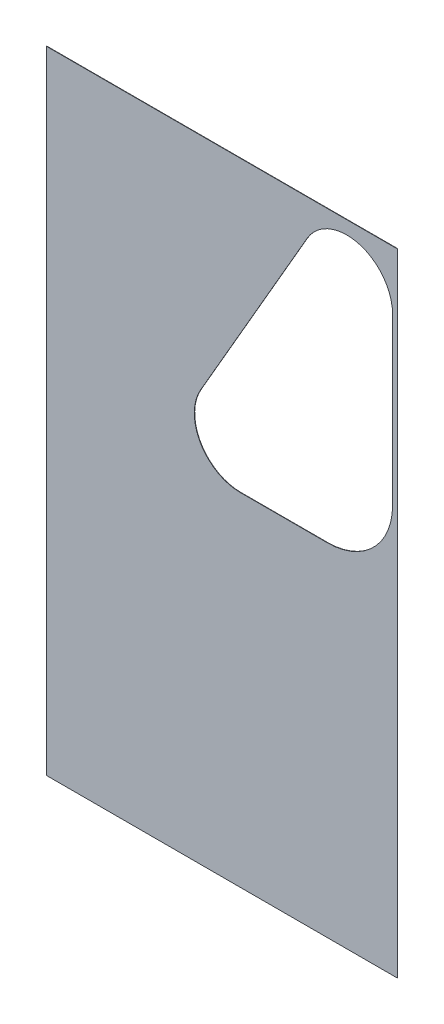
SolidWorks part; units mm, degrees
ref_plane "Front Plane" through (0, 0, 0) normal (0, 0, 1) x (1, 0, 0)
ref_plane "Top Plane" through (0, 0, 0) normal (0, 1, 0) x (1, 0, 0)
ref_plane "Right Plane" through (0, 0, 0) normal (1, 0, 0) x (0, 0, -1)
sketch "Sketch1" plane through (0, 0, 0) normal (0, 0, 1) x (1, 0, 0)
  line L1 (0, 0) -> (903, 0)
  line L2 (0, 0) -> (0, 1625)
  line L3 (0, 1625) -> (903, 1625)
  line L4 (903, 0) -> (903, 1625)
  dimension "D1" = 903
  dimension "D2" = 1625
extrude "Boss-Extrude1" add sketch "Sketch1" along normal blind 1
extrude "Cut-Extrude1" cut sketch "Sketch2" against normal through all
sketch "Sketch2" plane through (-119.4366, -43.0714, 1) normal (0, 0, 1) x (1, 0, 0)
  line L0 (1010.4366, 1516.0714) -> (1010.4366, 1091.0714)
  line L1 (842.4366, 923.0714) -> (618.1953, 923.0714)
  line L2 (516.0043, 1100.0714) -> (790.2456, 1575.0714)
  arc A0 (1010.4366, 1091.0714) -> (842.4366, 923.0714) centre (842.4366, 1091.0714) cw
  arc A1 (618.1953, 923.0714) -> (516.0043, 1100.0714) centre (618.1953, 1041.0714) cw
  arc A2 (1010.4366, 1516.0714) -> (790.2456, 1575.0714) centre (892.4366, 1516.0714) ccw
